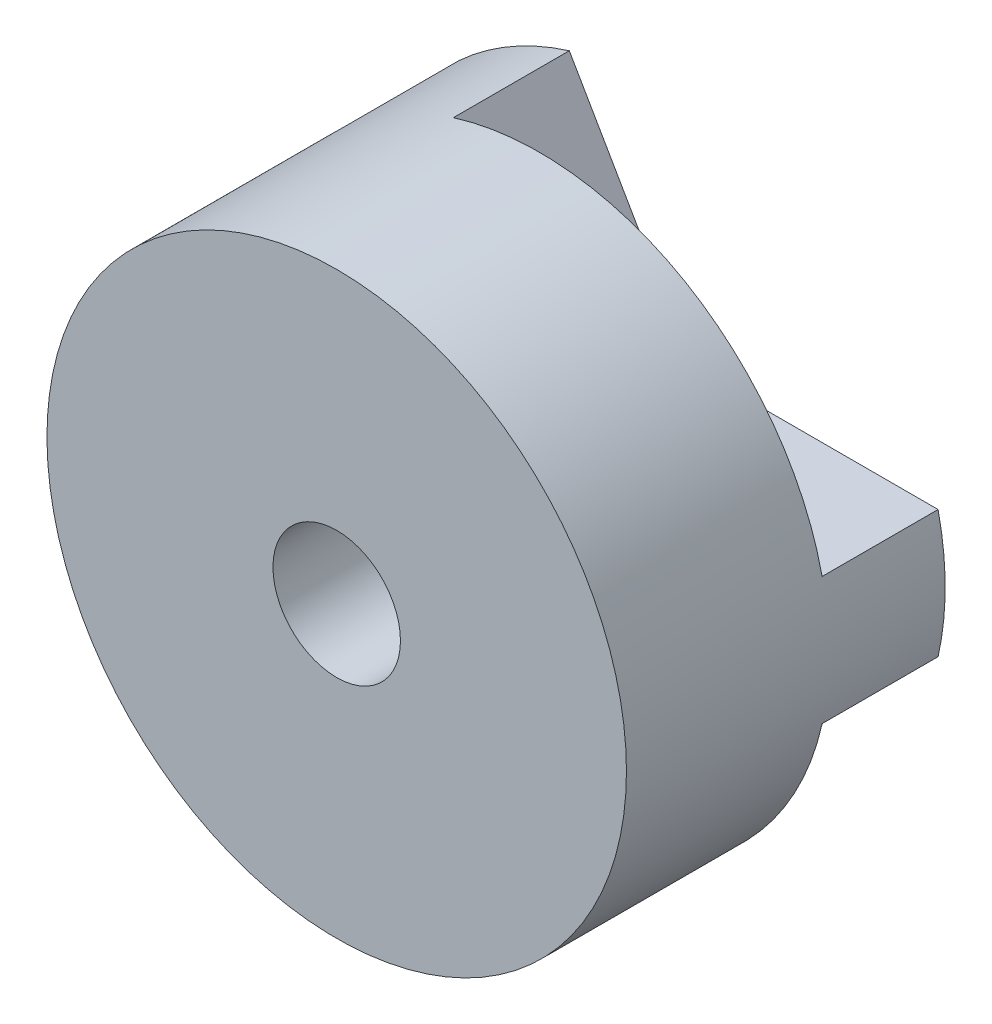
SolidWorks part; units mm, degrees
ref_plane "Front Plane" through (0, 0, 0) normal (0, 0, 1) x (1, 0, 0)
ref_plane "Top Plane" through (0, 0, 0) normal (0, 1, 0) x (1, 0, 0)
ref_plane "Right Plane" through (0, 0, 0) normal (1, 0, 0) x (0, 0, -1)
sketch "Sketch1" plane through (0, 0, 0) normal (0, 0, 1) x (1, 0, 0)
  circle A0 centre (0, 0) radius 50
  circle A1 centre (0, 0) radius 11
  dimension "D1" = 100
  dimension "D2" = 22
extrude "Boss-Extrude1" add sketch "Sketch1" along normal blind 55
sketch "Sketch3" plane through (0, 0, 0) normal (0, 0, -1) x (-1, 0, 0)
  line L0 (-48.775, -11) -> (-17.1455, -11)
  line L3 (-48.775, 11) -> (-17.1455, 11)
  line L6 (14.8612, 47.7404) -> (-0.9535, 20.3484)
  line L9 (33.9138, 36.7404) -> (18.099, 9.3484)
  line L12 (33.9138, -36.7404) -> (18.099, -9.3484)
  line L15 (14.8612, -47.7404) -> (-0.9535, -20.3484)
  arc A0 (-0.9535, -20.3484) -> (18.099, -9.3484) centre (0, 0) ccw
  arc A1 (18.099, 9.3484) -> (-0.9535, 20.3484) centre (0, 0) ccw
  circle A2 centre (0, 0) radius 50
  arc A3 (-48.775, -11) -> (14.8612, -47.7404) centre (0, 0) ccw
  arc A5 (33.9138, -36.7404) -> (33.9138, 36.7404) centre (0, 0) ccw
  arc A6 (14.8612, 47.7404) -> (-48.775, 11) centre (0, 0) ccw
  arc A7 (-17.1455, 11) -> (-17.1455, -11) centre (0, 0) ccw
  point P0 (14.301, 24.7701)
  point P1 (-28.602, 0)
  point P16 (14.301, -24.7701)
  point P21 (0, 0)
  dimension "D2" = 0
  dimension "D1" = 3
extrude "Cut-Extrude2" cut sketch "Sketch3" against normal blind 20
